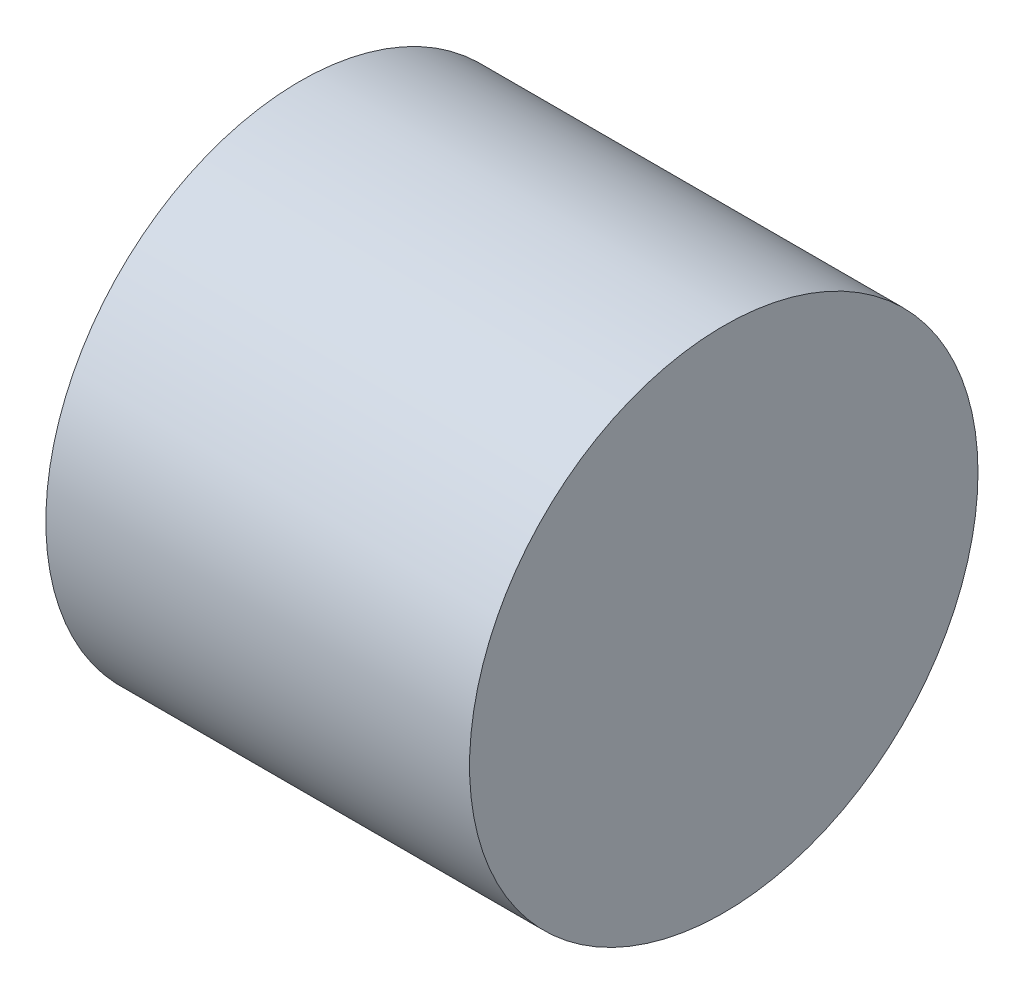
SolidWorks part; units mm, degrees
ref_plane "Ön Düzlem" through (0, 0, 0) normal (0, 0, 1) x (1, 0, 0)
ref_plane "Üst Düzlem" through (0, 0, 0) normal (0, 1, 0) x (1, 0, 0)
ref_plane "Sağ Düzlem" through (0, 0, 0) normal (1, 0, 0) x (0, 0, -1)
sketch "Sketch1" plane through (0, 0, 0) normal (1, 0, 0) x (0, 0, -1)
  circle A0 centre (0, 0) radius 3
extrude "Boss-Extrude1" add sketch "Sketch1" along normal blind 5
